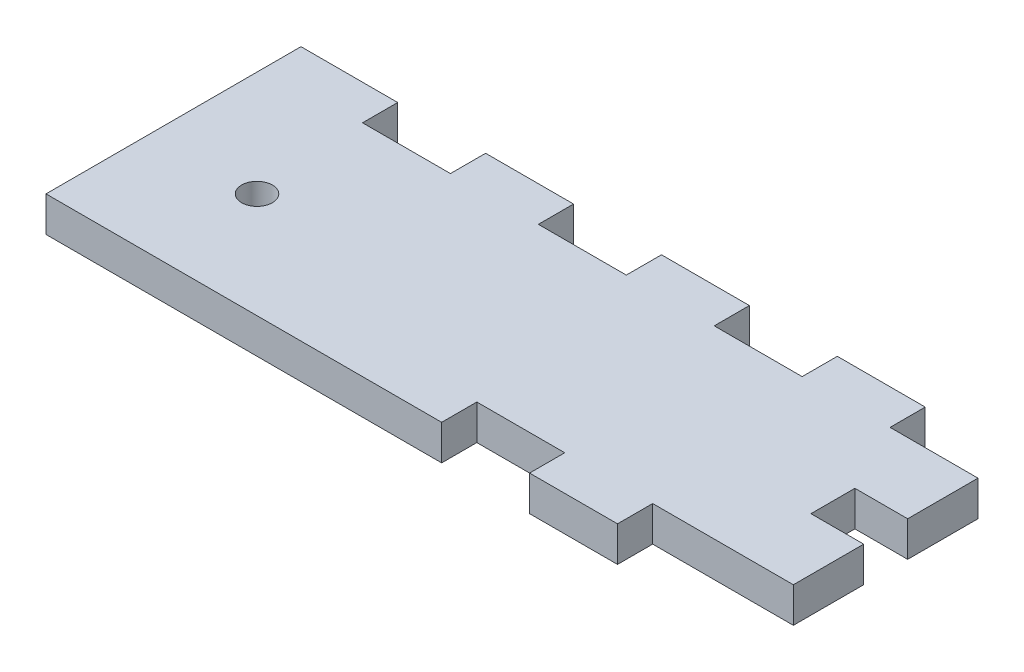
SolidWorks part; units mm, degrees
material "Maple"
ref_plane "Front Plane" through (0, 0, 0) normal (0, 0, 1) x (1, 0, 0)
ref_plane "Top Plane" through (0, 0, 0) normal (0, 1, 0) x (1, 0, 0)
ref_plane "Right Plane" through (0, 0, 0) normal (1, 0, 0) x (0, 0, -1)
sketch "Sketch1" plane through (0, 0, 0) normal (0, 1, 0) x (1, 0, 0)
  line L1 (0, 0) -> (75, 0)
  line L2 (0, 0) -> (0, -21)
  line L3 (0, -21) -> (75, -21)
  line L4 (75, 0) -> (75, -21)
  dimension "D1" = 75
  dimension "D2" = 21
extrude "Boss-Extrude1" add sketch "Sketch1" along normal blind 4
sketch "Sketch2" plane through (75, 0, 0) normal (1, 0, 0) x (0, 0, -1)
  line L0 (-21, 4) -> (0, 4) construction
  line L1 (-21, 4) -> (-13, 4)
  line L2 (-21, 4) -> (-21, 0)
  line L3 (-21, 0) -> (-13, 0)
  line L4 (-13, 4) -> (-13, 0)
  line L5 (-21, 0) -> (0, 0) construction
  line L6 (0, 4) -> (0, 0) construction
  line L7 (0, 4) -> (-8, 4)
  line L8 (0, 4) -> (0, 0)
  line L9 (0, 0) -> (-8, 0)
  line L10 (-8, 4) -> (-8, 0)
  line L11 (-21, 4) -> (-21, 0) construction
  dimension "D1" = 5
extrude "Boss-Extrude2" add sketch "Sketch2" along normal blind 6
sketch "Sketch3" plane through (0, 4, 0) normal (0, 1, 0) x (1, 0, 0)
  line L0 (81, 0) -> (0, 0) construction
  line L1 (71, 0) -> (61, 0)
  line L2 (71, 0) -> (71, 4)
  line L3 (71, 4) -> (61, 4)
  line L4 (61, 0) -> (61, 4)
  line L5 (81, 0) -> (81, -8) construction
  dimension "D1" = 10
  dimension "D2" = 4
  dimension "D3" = 10
extrude "Boss-Extrude3" add sketch "Sketch3" against normal through all
pattern_linear "LPattern1" count 4 spacing 20 along (-1, 0, 0) of "Boss-Extrude3"
sketch "Sketch4" plane through (0, 4, 0) normal (0, 1, 0) x (1, 0, 0)
  line L1 (1, 4) -> (0, 4)
  line L2 (1, 4) -> (1, 0)
  line L3 (1, 0) -> (0, 0)
  line L4 (0, 4) -> (0, 0)
extrude "Boss-Extrude4" add sketch "Sketch4" against normal through all
sketch "Sketch5" plane through (0, 4, 0) normal (0, 1, 0) x (1, 0, 0)
  line L0 (0, 4) -> (0, -21) construction
  line L1 (0, -21) -> (45, -21)
  line L2 (0, -21) -> (0, -25)
  line L3 (0, -25) -> (45, -25)
  line L4 (45, -21) -> (45, -25)
  line L5 (0, -21) -> (81, -21) construction
  line L7 (55, -25) -> (65, -25)
  line L8 (55, -25) -> (55, -21)
  line L9 (55, -21) -> (65, -21)
  line L10 (65, -25) -> (65, -21)
  dimension "D1" = 4
  dimension "D2" = 45
  dimension "D3" = 10
  dimension "D4" = 10
extrude "Boss-Extrude5" add sketch "Sketch5" against normal through all
sketch "Sketch6" plane through (0, 4, 0) normal (0, 1, 0) x (1, 0, 0)
  line L0 (0, -25) -> (45, -25) construction
  line L1 (0, 4) -> (0, -25) construction
  circle A0 centre (12, -13) radius 1.75
  dimension "D3" = 3.5
  dimension "D1" = 12
  dimension "D2" = 12
extrude "Cut-Extrude1" cut sketch "Sketch6" against normal through all
